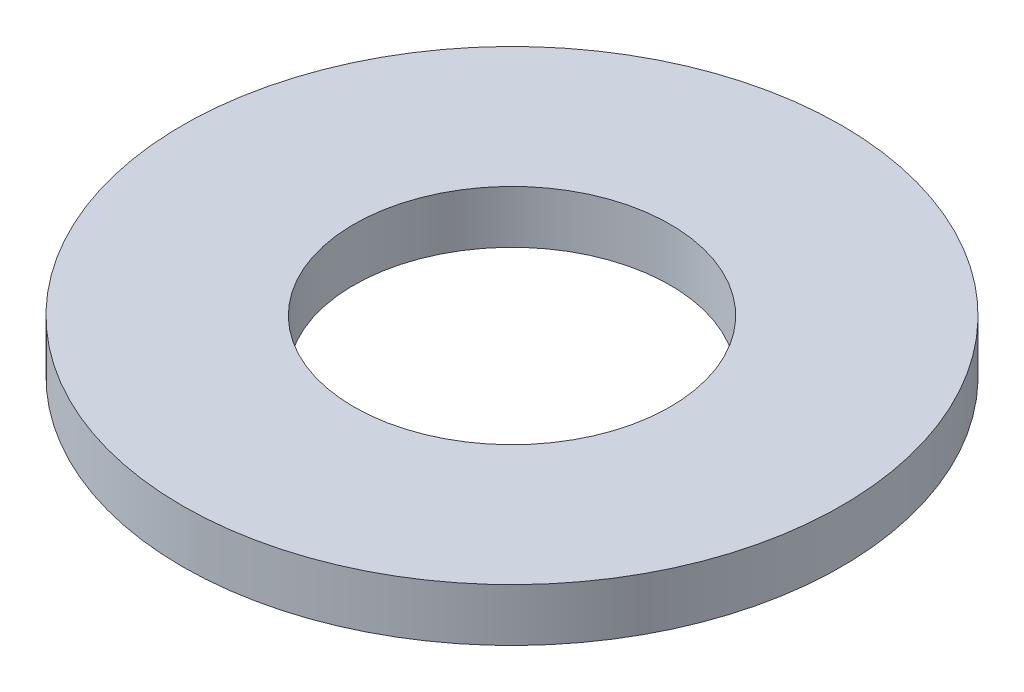
SolidWorks part; units mm, degrees
ref_plane "Front" through (0, 0, 0) normal (0, 0, 1) x (1, 0, 0)
ref_plane "Base" through (0, 0, 0) normal (0, 1, 0) x (1, 0, 0)
ref_plane "Side" through (0, 0, 0) normal (1, 0, 0) x (0, 0, -1)
sketch "Sketch1" plane through (0, 0, 0) normal (0, 1, 0) x (1, 0, 0)
  circle A0 centre (0, 0) radius 3
  circle A1 centre (0, 0) radius 6.25
  dimension "ID" = 6
  dimension "OD" = 12.5
extrude "Base-Extrude" add sketch "Sketch1" along normal mid plane 1
